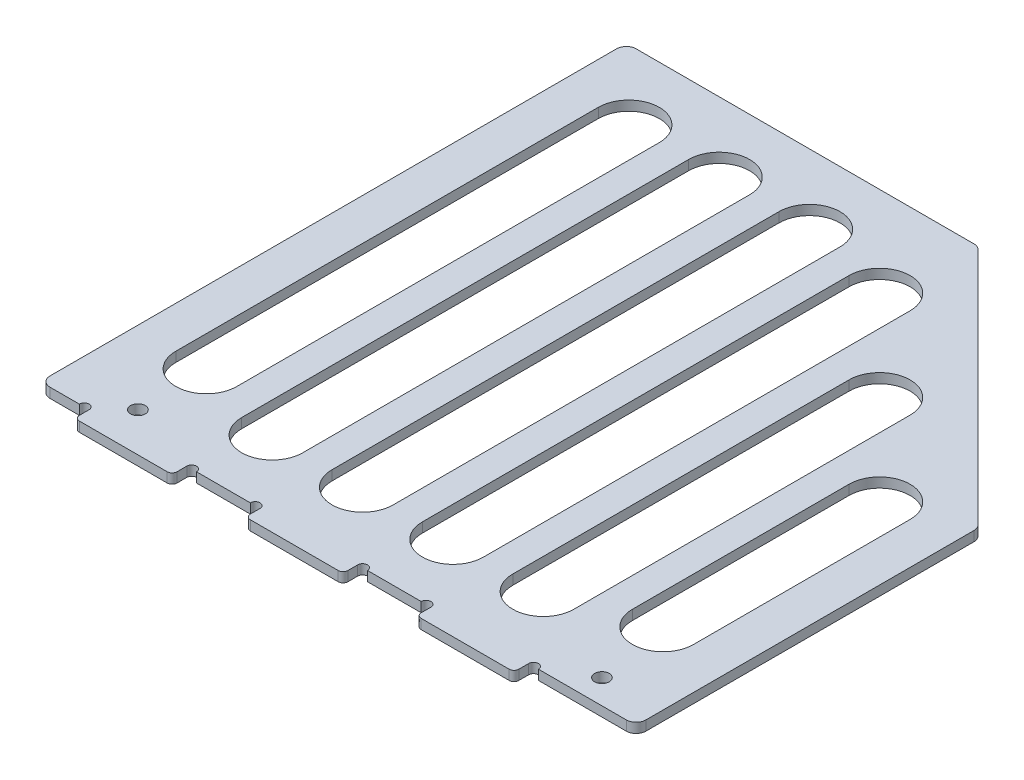
SolidWorks part; units mm, degrees
material "Thornel Mat VMA"
ref_plane "前视基准面" through (0, 0, 0) normal (0, 0, 1) x (1, 0, 0)
ref_plane "上视基准面" through (0, 0, 0) normal (0, 1, 0) x (1, 0, 0)
ref_plane "右视基准面" through (0, 0, 0) normal (1, 0, 0) x (0, 0, -1)
sketch "草图1" plane through (0, 0, 0) normal (0, 1, 0) x (1, 0, 0)
  line L0 (0, 0) -> (0, 70)
  line L1 (0, 70) -> (-50, 120)
  line L2 (-50, 120) -> (-122, 120)
  line L3 (-122, 120) -> (-122, 0)
  line L4 (-122, 0) -> (-112, 0)
  line L5 (-112, 0) -> (-112, -3)
  line L6 (-112, -3) -> (-92, -3)
  line L7 (-92, -3) -> (-92, 0)
  line L8 (-77, 0) -> (-77, -3)
  line L9 (-77, -3) -> (-57, -3)
  line L10 (-57, -3) -> (-57, 0)
  line L11 (-42, 0) -> (-42, -3)
  line L12 (-42, -3) -> (-22, -3)
  line L13 (-22, -3) -> (-22, 0)
  line L14 (-22, 0) -> (0, 0)
  line L15 (-57, 0) -> (-42, 0)
  line L16 (-92, 0) -> (-77, 0)
  line L17 (-107, 5) -> (-12, 5) construction
  circle A0 centre (-12, 5) radius 1.5
  circle A2 centre (-107, 5) radius 1.5
  dimension "D11" = 3
  dimension "D12" = 10
  dimension "D13" = 5
  dimension "D10" = 95
  dimension "D1" = 3
  dimension "D2" = 20
  dimension "D3" = 15
  dimension "D4" = 3
  dimension "D5" = 22
  dimension "D6" = 10
  dimension "D7" = 135
  dimension "D8" = 120
  dimension "D9" = 50
extrude "凸台-拉伸1" add sketch "草图1" along normal blind 2
sketch "草图2" plane through (0, 2, 0) normal (0, 1, 0) x (1, 0, 0)
  line L0 (-122, 0) -> (-112, 0) construction
  line L1 (-92, 0) -> (-77, 0) construction
  line L2 (-57, 0) -> (-42, 0) construction
  line L3 (-22, 0) -> (0, 0) construction
  circle A0 centre (-113, 0) radius 1
  circle A1 centre (-91, 0) radius 1
  circle A2 centre (-78, 0) radius 1
  circle A3 centre (-56, 0) radius 1
  circle A4 centre (-43, 0) radius 1
  circle A5 centre (-21, 0) radius 1
  dimension "D1" = 2
extrude "切除-拉伸1" cut sketch "草图2" against normal through all
sketch "草图3" plane through (0, 2, 0) normal (0, 1, 0) x (1, 0, 0)
  line L0 (-107.25, 105.75) -> (-107.25, 19.25) construction
  line L1 (-101, 105.75) -> (-101, 19.25)
  line L2 (-113.5, 105.75) -> (-113.5, 19.25)
  line L3 (-122, 120) -> (-122, 0) construction
  line L4 (-88.75, 105.75) -> (-88.75, 14.25) construction
  line L5 (-82.5, 105.75) -> (-82.5, 14.25)
  line L6 (-95, 105.75) -> (-95, 14.25)
  line L7 (-70.25, 105.75) -> (-70.25, 14.25) construction
  line L8 (-64, 105.75) -> (-64, 14.25)
  line L9 (-76.5, 105.75) -> (-76.5, 14.25)
  line L10 (-116, 8) -> (-13.3299, 8) construction
  line L11 (-122, 0) -> (-114, 0) construction
  line L12 (-51.75, 101.5975) -> (-51.75, 14.25) construction
  line L13 (-45.5, 101.5975) -> (-45.5, 14.25)
  line L14 (-58, 101.5975) -> (-58, 14.25)
  line L15 (-33.25, 83.0975) -> (-33.25, 14.25) construction
  line L16 (-27, 83.0975) -> (-27, 14.25)
  line L17 (-39.5, 83.0975) -> (-39.5, 14.25)
  line L18 (-14.75, 64.5975) -> (-14.75, 20.25) construction
  line L19 (-8.5, 64.5975) -> (-8.5, 20.25)
  line L20 (-21, 64.5975) -> (-21, 20.25)
  line L27 (-5.6569, 64.3431) -> (-53.3137, 112)
  line L28 (-53.3137, 112) -> (-122, 112)
  line L29 (-5.6569, 64.3431) -> (-53.3137, 112) construction
  line L30 (-53.3137, 112) -> (-122, 112) construction
  arc A0 (-101, 105.75) -> (-113.5, 105.75) centre (-107.25, 105.75) ccw
  arc A1 (-113.5, 19.25) -> (-101, 19.25) centre (-107.25, 19.25) ccw
  arc A2 (-82.5, 105.75) -> (-95, 105.75) centre (-88.75, 105.75) ccw
  arc A3 (-95, 14.25) -> (-82.5, 14.25) centre (-88.75, 14.25) ccw
  arc A4 (-64, 105.75) -> (-76.5, 105.75) centre (-70.25, 105.75) ccw
  arc A5 (-76.5, 14.25) -> (-64, 14.25) centre (-70.25, 14.25) ccw
  arc A6 (-45.5, 101.5975) -> (-58, 101.5975) centre (-51.75, 101.5975) ccw
  arc A7 (-58, 14.25) -> (-45.5, 14.25) centre (-51.75, 14.25) ccw
  arc A8 (-27, 83.0975) -> (-39.5, 83.0975) centre (-33.25, 83.0975) ccw
  arc A9 (-39.5, 14.25) -> (-27, 14.25) centre (-33.25, 14.25) ccw
  arc A10 (-8.5, 64.5975) -> (-21, 64.5975) centre (-14.75, 64.5975) ccw
  arc A11 (-21, 20.25) -> (-8.5, 20.25) centre (-14.75, 20.25) ccw
  point P2 (-107.25, 62.5)
  point P11 (-88.75, 60)
  point P16 (-70.25, 60)
  point P27 (-51.75, 57.9237)
  point P28 (-107.25, 19.4457)
  point P35 (-33.25, 48.6737)
  point P42 (-14.75, 42.4237)
  point P49 (-107.25, 13)
  point P50 (-21, 42.4237)
  point P51 (-14.75, 14)
  dimension "D1" = 12.5
  dimension "D2" = 8.5
  dimension "D3" = 6
  dimension "D4" = 6
  dimension "D5" = 8
  dimension "D6" = 5
  dimension "D7" = 6
  dimension "D8" = 6
  dimension "D9" = 6
  dimension "D10" = 6
  dimension "D11" = 8
extrude "切除-拉伸2" cut sketch "草图3" against normal through all
fillet "圆角1" radius 2 5 edges at (-122, 1, 0) (0, 1, 0) (0, 1, -70) (-50, 1, -120) (-122, 1, -120)
fillet "圆角2" radius 1 6 edges at (-22, 1, 3) (-42, 1, 3) (-57, 1, 3) (-77, 1, 3) (-92, 1, 3) (-112, 1, 3)
